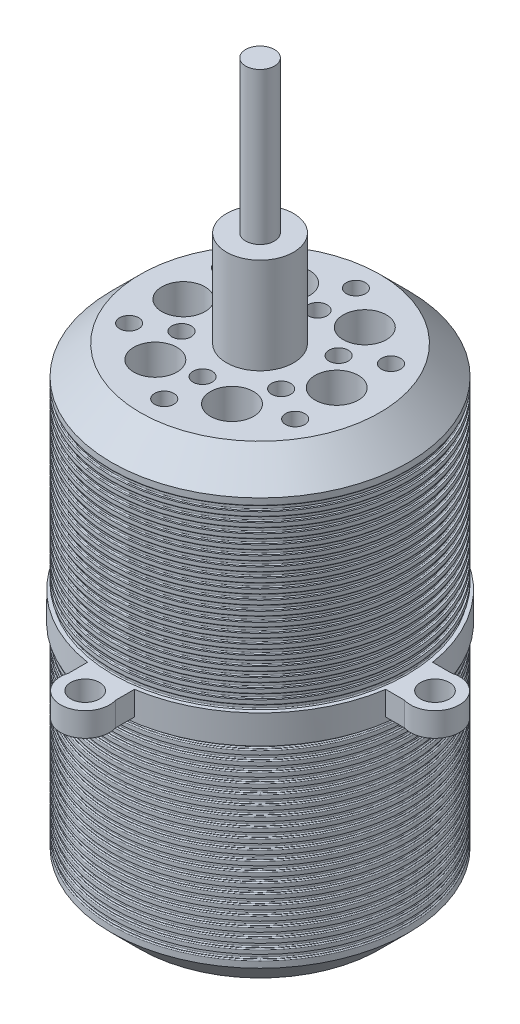
SolidWorks part; units mm, degrees
material "Plain Carbon Steel"
ref_plane "Front Plane" through (0, 0, 0) normal (0, 0, 1) x (1, 0, 0)
ref_plane "Top Plane" through (0, 0, 0) normal (0, 1, 0) x (1, 0, 0)
ref_plane "Right Plane" through (0, 0, 0) normal (1, 0, 0) x (0, 0, -1)
sketch "Sketch1" plane through (0, 0, 0) normal (0, 1, 0) x (1, 0, 0)
  circle A0 centre (0, 0) radius 15.5
  dimension "D1" = 31
extrude "Boss-Extrude1" add sketch "Sketch1" along normal blind 48.5
chamfer "Chamfer2" distance 3 angle 45 2 edges at (0, 0, 15.5) (0, 48.5, 15.5)
sketch "Sketch2" plane through (0, 48.5, 0) normal (0, 1, 0) x (1, 0, 0)
  circle A0 centre (0, 0) radius 3.5
  dimension "D1" = 7
extrude "Boss-Extrude2" add sketch "Sketch2" along normal blind 10
sketch "Sketch3" plane through (0, 58.5, 0) normal (0, 1, 0) x (1, 0, 0)
  circle A0 centre (0, 0) radius 1.5
  dimension "D1" = 3
extrude "Boss-Extrude3" add sketch "Sketch3" along normal blind 15.82
ref_plane "Plane1" through (0, 26.25, 0) normal (0, 1, 0) x (1, 0, 0)
sketch "Sketch4" plane through (0, 26.25, 0) normal (0, 1, 0) x (1, 0, 0)
  line L0 (0, 0) -> (0, 21.5908) construction
  line L1 (-2.4469, 15.3056) -> (-2.4469, 17.5099)
  line L2 (2.4469, 15.3056) -> (2.4469, 17.5099)
  line L3 (-2.4469, 15.3056) -> (2.4469, 15.3056)
  line L4 (15.3056, 2.4469) -> (17.5099, 2.4469)
  line L5 (15.3056, -2.4469) -> (17.5099, -2.4469)
  line L6 (15.3056, 2.4469) -> (15.3056, -2.4469)
  line L7 (2.4469, -15.3056) -> (2.4469, -17.5099)
  line L8 (-2.4469, -15.3056) -> (-2.4469, -17.5099)
  line L9 (2.4469, -15.3056) -> (-2.4469, -15.3056)
  line L10 (-15.3056, -2.4469) -> (-17.5099, -2.4469)
  line L11 (-15.3056, 2.4469) -> (-17.5099, 2.4469)
  line L12 (-15.3056, -2.4469) -> (-15.3056, 2.4469)
  circle A0 centre (0, 0) radius 15.5 construction
  circle A1 centre (0, 0) radius 15.5 construction
  arc A2 (-2.4469, 17.5099) -> (2.4469, 17.5099) centre (0, 18.25) cw
  circle A3 centre (0, 18.25) radius 1.5
  arc A4 (17.5099, 2.4469) -> (17.5099, -2.4469) centre (18.25, 0) cw
  circle A5 centre (18.25, 0) radius 1.5
  arc A6 (2.4469, -17.5099) -> (-2.4469, -17.5099) centre (0, -18.25) cw
  circle A7 centre (0, -18.25) radius 1.5
  arc A8 (-17.5099, -2.4469) -> (-17.5099, 2.4469) centre (-18.25, 0) cw
  circle A9 centre (-18.25, 0) radius 1.5
  point P8 (0, 15.5)
  dimension "D1" = 3
  dimension "D4" = 2.5564
  dimension "D2" = 18.25
  dimension "D3" = 4
extrude "Boss-Extrude4" add sketch "Sketch4" against normal blind 2.5
sketch "Sketch5" plane through (0, 48.5, 0) normal (0, 1, 0) x (1, 0, 0)
  line L0 (0, 0) -> (0, 12.5) construction
  circle A0 centre (0, 0) radius 12.5 construction
  circle A1 centre (0, 6) radius 1
  circle A2 centre (0, 10) radius 1
  circle A3 centre (0, 0) radius 1.5 construction
  circle A4 centre (0.0005, 0.0009) radius 1.5 construction
  circle A5 centre (5.1967, 3.0009) radius 1
  circle A6 centre (8.6608, 5.0009) radius 1
  circle A7 centre (0.0015, 0.0009) radius 1.5 construction
  circle A8 centre (5.1977, -2.9991) radius 1
  circle A9 centre (8.6618, -4.9991) radius 1
  circle A10 centre (0.002, 0) radius 1.5 construction
  circle A11 centre (0.002, -6) radius 1
  circle A12 centre (0.002, -10) radius 1
  circle A13 centre (0.0015, -0.0009) radius 1.5 construction
  circle A14 centre (-5.1947, -3.0009) radius 1
  circle A15 centre (-8.6588, -5.0009) radius 1
  circle A16 centre (0.0005, -0.0009) radius 1.5 construction
  circle A17 centre (-5.1957, 2.9991) radius 1
  circle A18 centre (-8.6598, 4.9991) radius 1
  dimension "D1" = 2
  dimension "D2" = 2
  dimension "D3" = 10
  dimension "D4" = 6
  dimension "D5" = 6
extrude "Cut-Extrude1" cut sketch "Sketch5" against normal blind 3
sketch "Sketch6" plane through (0, 26.25, 0) normal (0, 1, 0) x (1, 0, 0)
  circle A0 centre (0, 0) radius 15.75
  circle A2 centre (0, 0) radius 15.5
  dimension "D1" = 31.5
  dimension "D2" = 31
extrude "Boss-Extrude6" add sketch "Sketch6" against normal blind 3
sketch "Sketch7" plane through (0, 48.5, 0) normal (0, 1, 0) x (1, 0, 0)
  circle A0 centre (8, 0) radius 2.25
  circle A1 centre (4, -6.9282) radius 2.25
  circle A2 centre (-4, -6.9282) radius 2.25
  circle A3 centre (-8, 0) radius 2.25
  circle A4 centre (-4, 6.9282) radius 2.25
  circle A5 centre (4, 6.9282) radius 2.25
  dimension "D1" = 4.5
  dimension "D2" = 8
  dimension "D3" = 6
extrude "Cut-Extrude2" cut sketch "Sketch7" against normal blind 23
sketch "Sketch8" plane through (0, 26.25, 0) normal (0, 1, 0) x (1, 0, 0)
  circle A0 centre (0, 0) radius 15.7389
  circle A1 centre (0, 0) radius 15.2389
  dimension "D1" = 0.5
extrude "Cut-Extrude3" cut sketch "Sketch8" along normal blind 0.5
fillet "Fillet1" radius 0.1 3 edges at (0, 26.75, 15.2389) (0, 26.75, 15.5) (0, 26.25, 15.2389)
pattern_linear "LPattern1" count 19 spacing 1 along (0, 1, 0) of "Cut-Extrude3", "Fillet1"
sketch "Sketch9" plane through (0, 23.25, 0) normal (0, -1, 0) x (1, 0, 0)
  circle A0 centre (0, 0) radius 15.75
  circle A1 centre (0, 0) radius 15.25
  circle A2 centre (0, 0) radius 15.75 construction
  dimension "D1" = 0.5
extrude "Cut-Extrude4" cut sketch "Sketch9" along normal blind 0.5
fillet "Fillet2" radius 0.1 3 edges at (0, 22.75, -15.5) (0, 22.75, -15.25) (0, 23.25, -15.25)
pattern_linear "LPattern2" count 20 spacing 1 along (0, -1, 0) of "Fillet2", "Cut-Extrude4"
